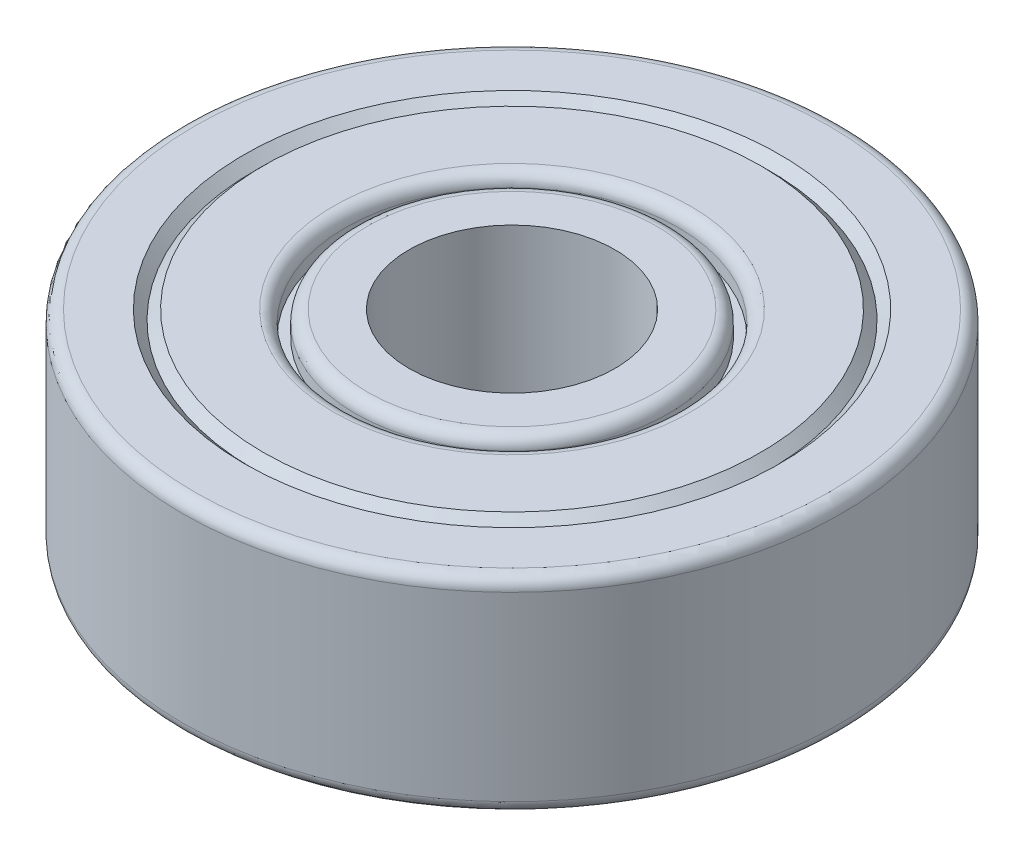
SolidWorks part; units mm, degrees
ref_plane "Front Plane" through (0, 0, 0) normal (0, 0, 1) x (1, 0, 0)
ref_plane "Top Plane" through (0, 0, 0) normal (0, 1, 0) x (1, 0, 0)
ref_plane "Right Plane" through (0, 0, 0) normal (1, 0, 0) x (0, 0, -1)
sketch "Sketch1" plane through (0, 0, 0) normal (0, 0, 1) x (1, 0, 0)
  line L0 (0, 0) -> (0, -8.6859) construction
  line L1 (-2.5, -3.6859) -> (-2.5, -8.6859)
  line L2 (-2.5, -8.6859) -> (-8, -8.6859) construction
  line L3 (-8, -8.6859) -> (-8, -3.6859)
  line L4 (-8, -3.6859) -> (-2.5, -3.6859) construction
  line L5 (-8, -3.6859) -> (-6.5, -3.6859)
  line L6 (-6.5, -3.6859) -> (-6.2664, -3.9195)
  line L7 (-6.2664, -3.9195) -> (-6.0328, -3.6859)
  line L8 (-6.0328, -3.6859) -> (-4.0328, -3.6859)
  line L9 (-4.0328, -3.6859) -> (-4.0328, -4.2859)
  line L10 (-4.0328, -4.2859) -> (-3.8, -4.2859)
  line L11 (-3.8, -4.2859) -> (-3.8, -3.6859)
  line L12 (-3.8, -3.6859) -> (-2.5, -3.6859)
  line L13 (-8, -8.6859) -> (-6.5, -8.6859)
  line L14 (-6.5, -8.6859) -> (-6.2664, -8.4523)
  line L15 (-6.2664, -8.4523) -> (-6.0328, -8.6859)
  line L16 (-6.0328, -8.6859) -> (-4.0328, -8.6859)
  line L17 (-4.0328, -8.6859) -> (-4.0328, -8.0859)
  line L18 (-4.0328, -8.0859) -> (-3.8, -8.0859)
  line L19 (-3.8, -8.0859) -> (-3.8, -8.6859)
  line L20 (-3.8, -8.6859) -> (-2.5, -8.6859)
  dimension "D1" = 2.5
  dimension "D2" = 8
  dimension "D3" = 5
  dimension "D4" = 1.5
  dimension "D5" = 2
  dimension "D6" = 1.3
  dimension "D7" = 0.6
revolve "Revolve1" add sketch "Sketch1" angle 360 about L0
fillet "Fillet1" radius 0.3 6 edges at (0, -8.6859, 3.8) (0, -8.6859, 4.0328) (0, -8.6859, 8) (0, -3.6859, 8) (0, -3.6859, 4.0328) (0, -3.6859, 3.8)
